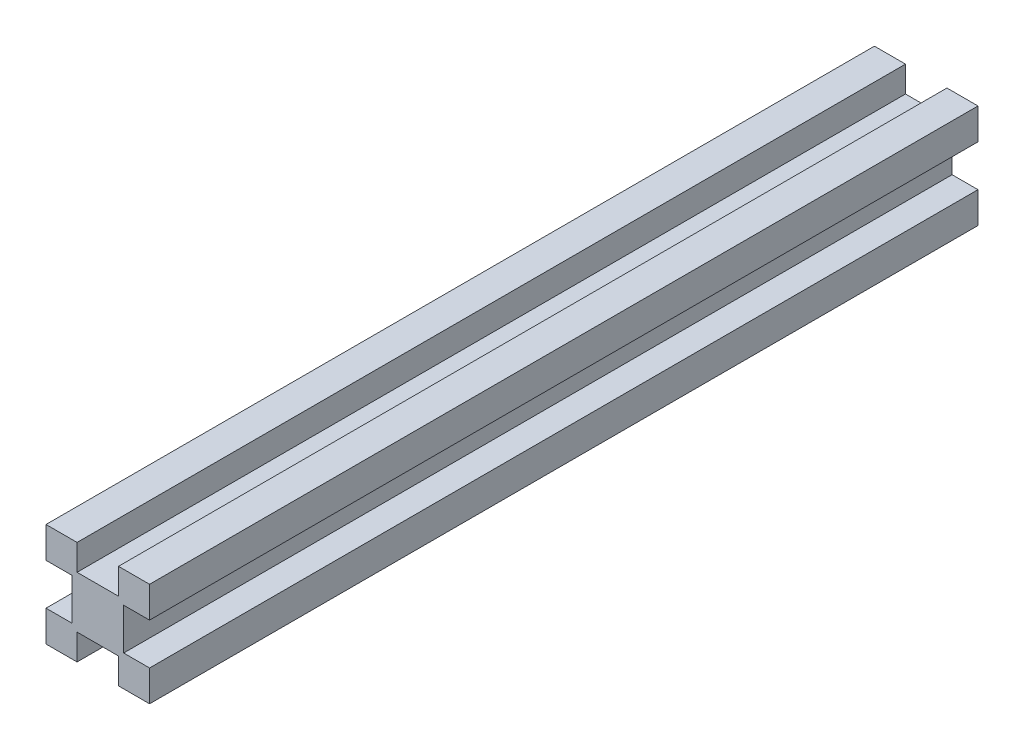
SolidWorks part; units mm, degrees
ref_plane "Alzado" through (0, 0, 0) normal (0, 0, 1) x (1, 0, 0)
ref_plane "Planta" through (0, 0, 0) normal (0, 1, 0) x (1, 0, 0)
ref_plane "Vista lateral" through (0, 0, 0) normal (1, 0, 0) x (0, 0, -1)
sketch "Croquis1" plane through (0, 0, 0) normal (0, 0, 1) x (1, 0, 0)
  line L1 (-23.5326, 14.5417) -> (-3.5326, 14.5417)
  line L2 (-23.5326, 14.5417) -> (-23.5326, -5.4583)
  line L3 (-23.5326, -5.4583) -> (-3.5326, -5.4583)
  line L4 (-3.5326, 14.5417) -> (-3.5326, -5.4583)
  line L5 (-23.5326, 14.5417) -> (-3.5326, -5.4583) construction
  line L6 (-23.5326, -5.4583) -> (-3.5326, 14.5417) construction
  point P0 (-13.5326, 4.5417)
  dimension "D1" = 20
extrude "Saliente-Extruir1" add sketch "Croquis1" along normal blind 160
sketch "Croquis2" plane through (0, 0, 160) normal (0, 0, 1) x (1, 0, 0)
  line L0 (-23.5326, 4.5417) -> (-3.5326, 4.5417) construction
  line L1 (-3.5326, 14.5417) -> (-23.5326, 14.5417) construction
  line L2 (-13.5326, 9.5417) -> (-17.5326, 9.5417)
  line L3 (-13.5326, 9.5417) -> (-9.5326, 9.5417)
  line L4 (-17.5326, 9.5417) -> (-17.5326, 14.5417)
  line L5 (-9.5326, 9.5417) -> (-9.5326, 14.5417)
  line L6 (-17.5326, 14.5417) -> (-9.5326, 14.5417)
  line L7 (-23.5326, 14.5417) -> (-23.5326, -5.4583) construction
  line L8 (-3.5326, -5.4583) -> (-3.5326, 14.5417) construction
  line L9 (-13.5326, 14.5417) -> (-13.5326, -5.4583) construction
  line L10 (-23.5326, -5.4583) -> (-3.5326, -5.4583) construction
  line L11 (-9.5326, -0.4583) -> (-9.5326, -5.4583)
  line L12 (-13.5326, -0.4583) -> (-9.5326, -0.4583)
  line L13 (-13.5326, -0.4583) -> (-17.5326, -0.4583)
  line L14 (-17.5326, -5.4583) -> (-9.5326, -5.4583)
  line L15 (-17.5326, -0.4583) -> (-17.5326, -5.4583)
  line L16 (-23.5326, 4.5417) -> (-23.5326, 8.5417)
  line L17 (-23.5326, 8.5417) -> (-18.5326, 8.5417)
  line L18 (-18.5326, 8.5417) -> (-18.5326, 0.5417)
  line L19 (-18.5326, 0.5417) -> (-23.5326, 0.5417)
  line L20 (-23.5326, 0.5417) -> (-23.5326, 4.5417)
  line L21 (-8.5326, 8.5417) -> (-8.5326, 0.5417)
  line L22 (-8.5326, 0.5417) -> (-3.5326, 0.5417)
  line L23 (-3.5326, 0.5417) -> (-3.5326, 4.5417)
  line L24 (-3.5326, 4.5417) -> (-3.5326, 8.5417)
  line L25 (-3.5326, 8.5417) -> (-8.5326, 8.5417)
  dimension "D1" = 4
  dimension "D2" = 5
extrude "Cortar-Extruir1" cut sketch "Croquis2" against normal blind 320
